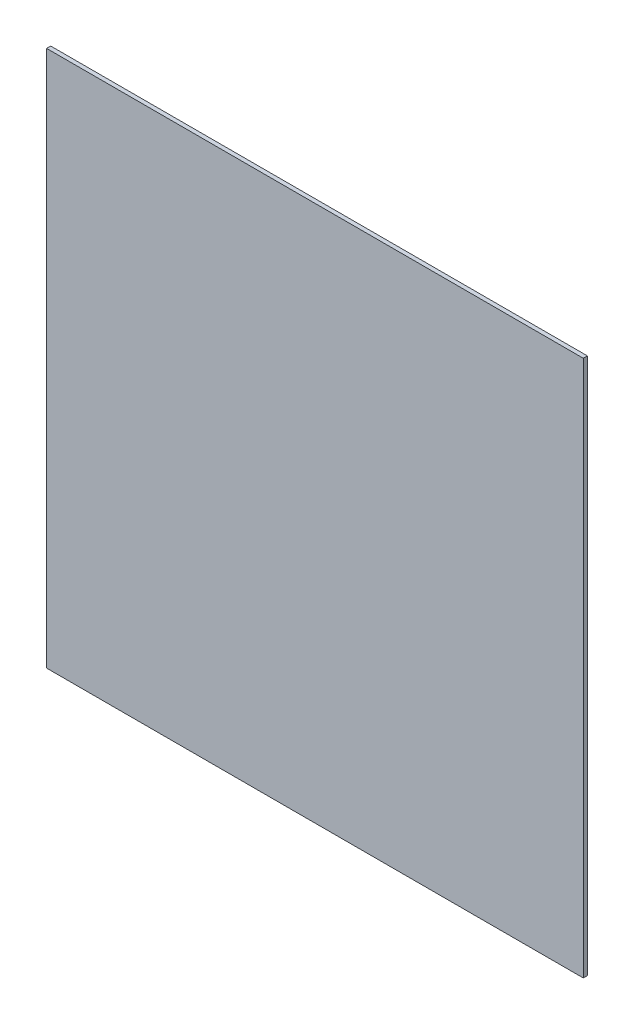
SolidWorks part; units mm, degrees
ref_plane "前基準面" through (0, 0, 0) normal (0, 0, 1) x (1, 0, 0)
ref_plane "上基準面" through (0, 0, 0) normal (0, 1, 0) x (1, 0, 0)
ref_plane "右基準面" through (0, 0, 0) normal (1, 0, 0) x (0, 0, -1)
sketch "草圖1" plane through (0, 0, 0) normal (0, 0, 1) x (1, 0, 0)
  line L1 (-195.5, 195.5) -> (195.5, 195.5)
  line L2 (-195.5, 195.5) -> (-195.5, -195.5)
  line L3 (-195.5, -195.5) -> (195.5, -195.5)
  line L4 (195.5, 195.5) -> (195.5, -195.5)
  line L5 (-195.5, 195.5) -> (195.5, -195.5) construction
  line L6 (-195.5, -195.5) -> (195.5, 195.5) construction
  point P0 (0, 0)
  dimension "D1" = 391
  dimension "D2" = 391
extrude "填料-伸長1" add sketch "草圖1" along normal blind 3
